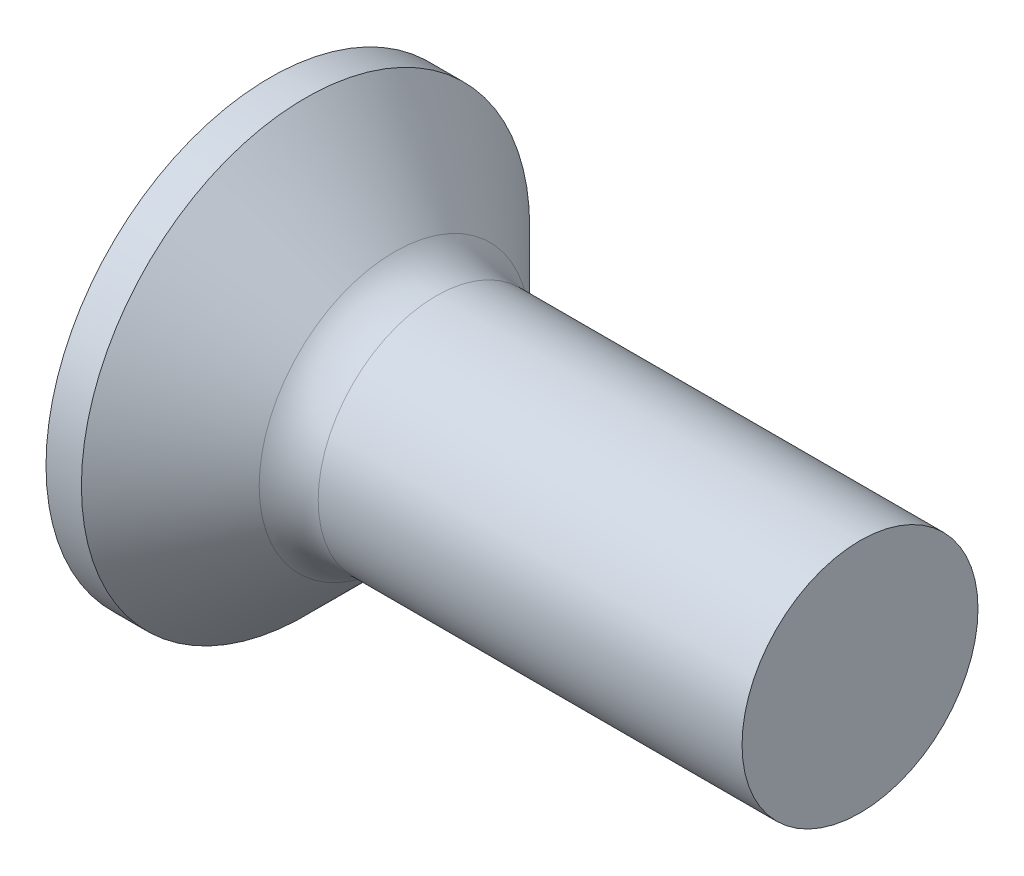
SolidWorks part; units mm, degrees
ref_plane "Plane1" through (0, 0, 0) normal (0, 0, 1) x (1, 0, 0)
ref_plane "Plane2" through (0, 0, 0) normal (0, 1, 0) x (1, 0, 0)
ref_plane "Plane3" through (0, 0, 0) normal (1, 0, 0) x (0, 0, -1)
sketch "BodySke" plane through (0, 0, 0) normal (0, 0, 1) x (1, 0, 0)
  line L0 (0, 0) -> (0, 1.9)
  line L1 (0, 1.9) -> (0.3, 1.9)
  line L2 (1.2, 1) -> (5, 1)
  line L3 (5, 1) -> (5, 0)
  line L4 (5, 0) -> (0, 0)
  line L5 (-6.35, 0) -> (82.55, 0) construction
  line L6 (1.2, -1) -> (5, -1) construction
  line L7 (0.3, -1.9) -> (1.2, -1) construction
  line L8 (0.3, 1.9) -> (1.2, 1)
  line L9 (0, -1.9) -> (0.3, -1.9) construction
  line L10 (1.6, 2.5875) -> (1.6, -6.9375) construction
  line L11 (0, 6.35) -> (0, -3.175) construction
  dimension "Diameter" = 2
  dimension "Length" = 5
  dimension "Head_ht" = 1.2
  dimension "Head_dia" = 3.8
  dimension "Head_ang" = 90
  dimension "D6" = 0.3
  dimension "Advance" = 0.4
  dimension "Thread_nom" = 5
revolve "Base-Revolve" add sketch "BodySke"
cosmetic thread "ThreadCosmetic" [suppressed]
fillet "Fillet1" radius 0.5 1 edges at (1.2, 0, 1)
sketch "Sketch3" plane through (0, 0, 0) normal (-1, 0, 0) x (0, 0, 1)
  line L0 (-0.24, 0.95) -> (0.24, 0.95)
  line L1 (0.24, 0.95) -> (0.24, -0.95)
  line L2 (0.24, -0.95) -> (-0.24, -0.95)
  line L3 (-0.24, -0.95) -> (-0.24, 0.95)
  dimension "D1" = 0.95
  dimension "Cross_dia" = 1.9
  dimension "D2" = 0.24
  dimension "Cross_width" = 0.48
ref_plane "Plane4" through (1.2, 0, 0) normal (-1, 0, 0) x (0, 0, 1)
sketch "Sketch4" plane through (1.2, 0, 0) normal (-1, 0, 0) x (0, 0, 1)
  line L0 (-0.24, 0.3517) -> (0.24, 0.3517)
  line L3 (0.24, 0.3517) -> (0.24, -0.3517)
  line L4 (0.24, -0.3517) -> (-0.24, -0.3517)
  line L5 (-0.24, -0.3517) -> (-0.24, 0.3517)
  dimension "D1" = 0.48
  dimension "D2" = 0.7034
  dimension "D3" = 0.24
  dimension "D4" = 0.3517
loft "Recess" cut profiles "Sketch3", "Sketch4"
pattern_circular "RecPat" count 2 every 90 about axis through (0, 0, 0) along (1, 0, 0) of "Recess"
sketch "RecCorSke" plane through (0, 0, 0) normal (0, 0, 1) x (1, 0, 0)
  line L0 (-3.175, 0) -> (15.875, 0) construction
  line L2 (0, 0) -> (0, 0.4394)
  line L3 (0, 0.4394) -> (1.2, 0.3555)
  line L4 (1.2, 0.3555) -> (1.3155, 0)
  line L5 (1.3155, 0) -> (0, 0)
  dimension "Diameter" = 0.711
  dimension "Depth" = 1.2
  dimension "Draft_angle" = 4
  dimension "Bottom_angle" = 18
revolve "RecessCore" cut sketch "RecCorSke" angle 360 about L0
sketch "ThdSchSke" plane through (0, 0, 0) normal (0, 0, 1) x (1, 0, 0)
  line L0 (1.6, -0.774) -> (1.4418, -1)
  line L1 (1.6, -0.774) -> (1.7582, -1)
  line L2 (1.7582, -1) -> (1.7582, -1.25)
  line L3 (-3.175, 0) -> (5.1513, 0) construction
  line L5 (1.7582, -1.25) -> (1.4418, -1.25)
  line L6 (1.4418, -1.25) -> (1.4418, -1)
  line L7 (0, 1.9) -> (0, -1.9) construction
  dimension "Thread_minor" = 1.548
  dimension "Diameter" = 2
  dimension "Start" = 1.6
  dimension "SideAngle" = 55
  dimension "VeeAngle" = 70
  dimension "Overcut" = 2.5
revolve "ThreadSchematic" [suppressed] cut sketch "ThdSchSke" angle 360 about L3
pattern_linear "ThdSchPat" [suppressed]
equation "\"D1@Sketch3\" = \"Cross_dia@Sketch3\" / 2"
equation "\"D2@Sketch3\" = \"Cross_width@Sketch3\" / 2"
equation "\"Depth@RecCorSke\" = \"Cross_depth@Plane4\""
equation "\"D1@Sketch4\" = \"Cross_width@Sketch3\""
equation "\"D2@Sketch4\" = \"Cross_dia@Sketch3\" - 2.0 * \"Cross_depth@Plane4\" * tan(26.5  * 0.017453292)"
equation "\"D3@Sketch4\" = \"D1@Sketch4\" / 2"
equation "\"D4@Sketch4\" = \"D2@Sketch4\" / 2"
equation "\"Thread_length@ThreadCosmetic\" = ((sgn( (\"Length@BodySke\" - \"Advance@BodySke\" * 1.0 - \"Head_ht@BodySke\" ) - \"Thread_nom@BodySke\" )-1)*( (\"Length@BodySke\" - \"Advance@BodySke\" * 1.0 - \"Head_ht@BodySke\" ) - \"Thread_nom@BodySke\" ))/-2+ \"Thread_nom@BodySke\""
equation "\"Thread_minor@ThdSchSke\" = \"Thread_minor@ThreadCosmetic\""
equation "\"Diameter@ThdSchSke\" = \"Diameter@BodySke\""
equation "\"Overcut@ThdSchSke\" = \"Diameter@BodySke\" * 1.25"
equation "\"Start@ThdSchSke\" = 0.000001 + \"Length@BodySke\" - \"Thread_length@ThreadCosmetic\"  '---Countersunk---"
equation "\"Num_threads@ThdSchPat\" = int( \"Thread_length@ThreadCosmetic\" / \"Advance@BodySke\" + 0.999 )  + 1"
equation "\"Advance@ThdSchPat\" = \"Thread_length@ThreadCosmetic\" /  (\"Num_threads@ThdSchPat\" - 1) 'relax it"
